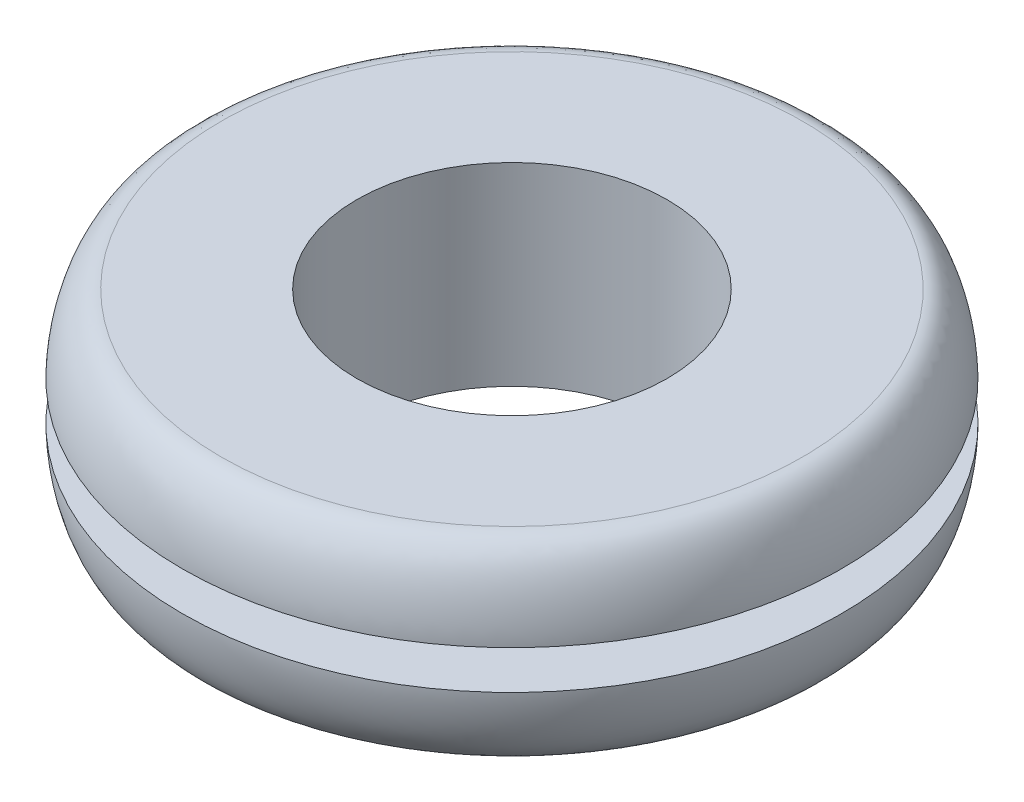
SolidWorks part; units mm, degrees
ref_plane "Front" through (0, 0, 0) normal (0, 0, 1) x (1, 0, 0)
ref_plane "Top" through (0, 0, 0) normal (0, 1, 0) x (1, 0, 0)
ref_plane "Right" through (0, 0, 0) normal (1, 0, 0) x (0, 0, -1)
sketch "Sketch1" plane through (0, 0, 0) normal (0, 0, 1) x (1, 0, 0)
  line L0 (-6.35, 3.9688) -> (-6.35, -3.9688)
  line L1 (-13.4937, 0.7937) -> (-10.3187, 0.7937)
  line L2 (-10.3187, 0.7937) -> (-10.3187, -0.7937)
  line L3 (-6.35, -3.9688) -> (-11.9062, -3.9688)
  line L4 (-6.35, 3.9688) -> (-11.9062, 3.9688)
  line L5 (-11.9062, 3.9688) -> (-11.9062, 0.7937) construction
  line L6 (-27.8997, 0) -> (0, 0) construction
  line L7 (55, 0) -> (-55, 0) construction
  line L8 (-13.4937, -0.7937) -> (-10.3187, -0.7937)
  line L9 (-13.4937, -0.056) -> (-13.4937, 2.4378) construction
  line L10 (-12.0259, 3.9688) -> (-10.1926, 3.9688) construction
  line L11 (0, 96.2646) -> (0, -76.2636) construction
  line L12 (0, -55) -> (0, 55) construction
  spline S0 degree 3 poles (-11.9062, 3.9688) (-13.052, 3.9688) (-13.4937, 1.8328) (-13.4937, 0.7937) knots 0 0 0 0 1 1 1 1
  spline S1 degree 3 poles (-11.9062, -3.9688) (-13.052, -3.9688) (-13.4937, -1.8328) (-13.4937, -0.7937) knots 0 0 0 0 1 1 1 1
  point P17 (-10.3187, 0)
  dimension "D1" = 1.5875
  dimension "D2" = 10.3187
  dimension "D3" = 6.35
  dimension "D4" = 7.9375
  dimension "D5" = 13.4937
revolve "Revolve1" add sketch "Sketch1" angle 360 about L11
